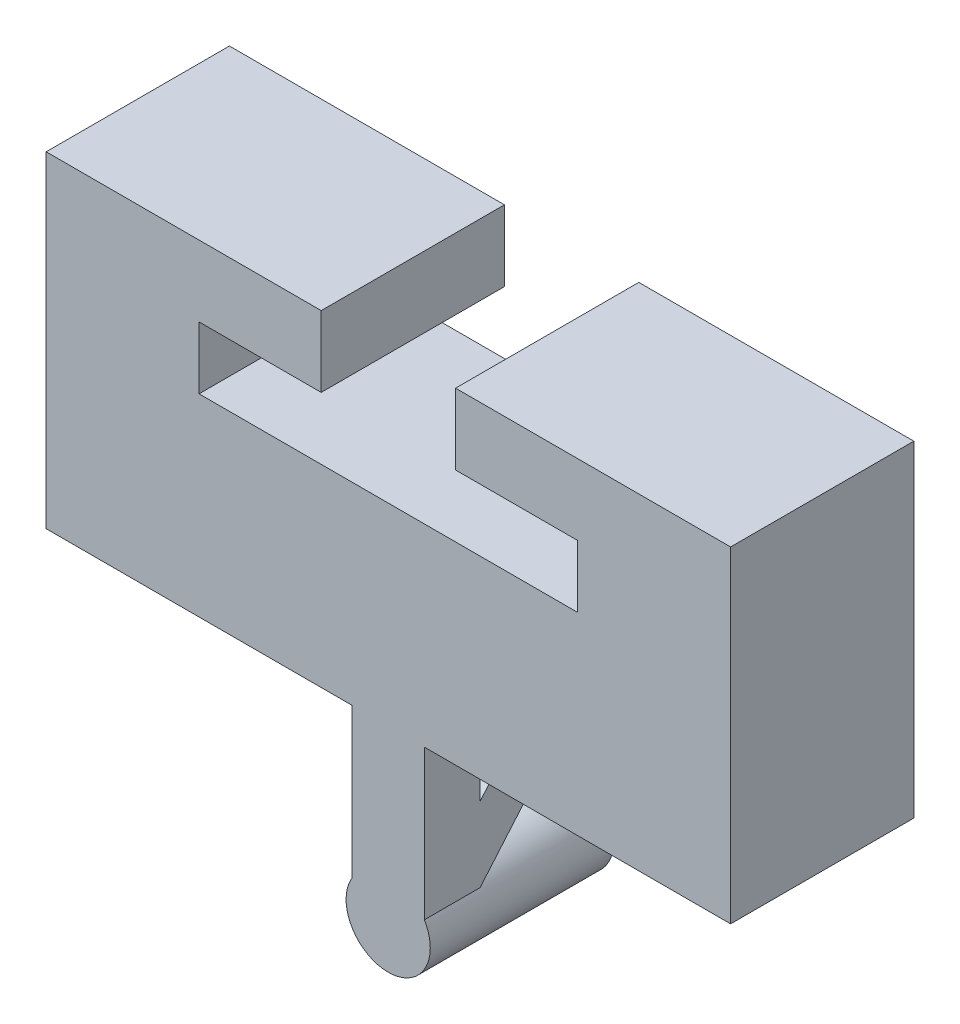
SolidWorks part; units mm, degrees
material "Nylon 101"
ref_plane "Front Plane" through (0, 0, 0) normal (0, 0, 1) x (1, 0, 0)
ref_plane "Top Plane" through (0, 0, 0) normal (0, 1, 0) x (1, 0, 0)
ref_plane "Right Plane" through (0, 0, 0) normal (1, 0, 0) x (0, 0, -1)
sketch "Sketch1" plane through (0, 0, 0) normal (0, 0, 1) x (1, 0, 0)
  line L0 (0, 0) -> (142.3195, 0)
  line L1 (142.3195, 0) -> (142.3195, 67.883)
  line L2 (142.3195, 67.883) -> (85.1297, 67.883)
  line L3 (85.1297, 67.883) -> (85.1297, 53.1441)
  line L4 (85.1297, 53.1441) -> (110.5297, 53.1441)
  line L5 (110.5297, 53.1441) -> (110.5297, 40.1901)
  line L6 (110.5297, 40.1901) -> (31.7897, 40.1901)
  line L7 (31.7897, 40.1901) -> (31.7897, 53.1441)
  line L8 (31.7897, 53.1441) -> (57.1897, 53.1441)
  line L9 (57.1897, 53.1441) -> (57.1897, 67.883)
  line L10 (57.1897, 67.883) -> (0, 67.883)
  line L11 (0, 67.883) -> (0, 0)
  dimension "D1" = 78.74
  dimension "D2" = 14.7389
  dimension "D3" = 14.7389
  dimension "D4" = 31.7897
  dimension "D5" = 40.1901
  dimension "D6" = 31.7897
  dimension "D7" = 25.4
  dimension "D8" = 25.4
  dimension "D9" = 12.954
  dimension "D10" = 12.954
extrude "Boss-Extrude1" add sketch "Sketch1" along normal blind 38.1
sketch "Sketch2" plane through (0, 0, 38.1) normal (0, 0, 1) x (1, 0, 0)
  line L0 (71.1597, 40.1901) -> (71.1597, 0) construction
  line L1 (110.5297, 40.1901) -> (31.7897, 40.1901) construction
  line L2 (0, 0) -> (142.3195, 0) construction
  circle A0 centre (71.12, -35.56) radius 8.7503
  dimension "D1" = 17.5006
  dimension "D2" = 35.56
extrude "Boss-Extrude2" add sketch "Sketch2" against normal blind 38.1
sketch "Sketch8" plane through (0, 0, 38.1) normal (0, 0, 1) x (1, 0, 0)
  line L0 (63.592, -40.0206) -> (63.592, 0)
  line L1 (0, 0) -> (142.3195, 0) construction
  line L2 (78.648, -40.0206) -> (78.648, 0)
  line L3 (78.648, 0) -> (63.592, 0)
  circle A0 centre (71.12, -35.56) radius 8.7503 construction
  circle A2 centre (71.12, -35.56) radius 8.7503
  arc A3 (63.592, -40.0206) -> (78.648, -40.0206) centre (71.12, -35.56) ccw
  dimension "D1" = 0
extrude "Boss-Extrude6" add sketch "Sketch8" against normal blind 11.5723
sketch "Sketch11" plane through (78.648, 0, 0) normal (1, 0, 0) x (0, 0, -1)
  line L0 (-26.5277, -31.0994) -> (0, 0)
  line L1 (0, 0) -> (-13.2639, 0)
  line L2 (-38.1, 0) -> (0, 0) construction
  line L3 (-13.2639, 0) -> (-26.5277, -15.5497)
  line L4 (-26.5277, -31.0994) -> (-26.5277, 0) construction
  line L5 (-26.5277, -15.5497) -> (-26.5277, -31.0994)
extrude "Boss-Extrude9" add sketch "Sketch11" against normal blind 15.24
equation "\"E\"= 470000"
equation "\"SF\"= 4"
equation "\"F\"= 250"
equation "\"Deflection\"= .005"
equation "\"IA\"= ( 5 * 500 * \"SF\" * 1 ) / ( 384 * \"E\" * \"Deflection\" )"
equation "\"Feature A Diameter \"= ( ( 64 * \"IA\" ) / pi ) ^ ( 1 / 4 )"
equation "\"Feature B Width\"= ( \"F\" * \"SF\" ) / ( \"E\" * \"Deflection\" * .934 )"
equation "\"IC\"= ( 5 * 500 * \"SF\" * ( 92.35 ) ) / ( 384 * \"E\" * \"Deflection\" )"
equation "\"Feature C height\"= ( ( 12 * \"IC\" ) / 3.1 ) ^ ( 1 / 3 )"
equation "\"Feature D width\"= ( \"F\" * \"SF\" * 1.5 ) / ( \"E\" * \"Deflection\" * .51 )"
equation "\"Feature E\"= ( \"F\" * \"SF\" * 1.5 ) / ( \"E\" * \"Deflection\" * 1.1 )"
equation "\"D3@Sketch1\"=\"Feature E\""
equation "\"D2@Sketch1\"=\"Feature E\""
equation "\"D4@Sketch1\"=\"Feature D width\""
equation "\"D6@Sketch1\"=\"Feature D width\" "
equation "\"D5@Sketch1\"=\"Feature C height\""
equation "\"D1@Boss-Extrude6\"=\"Feature B Width\""
